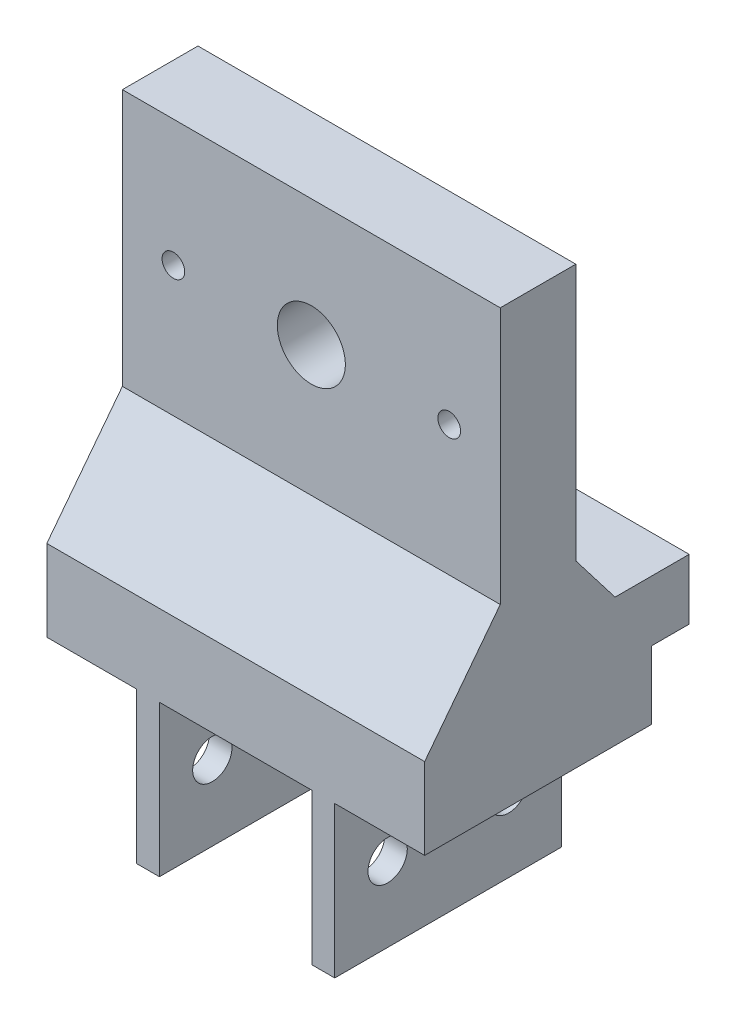
SolidWorks part; units mm, degrees
ref_plane "前视基准面" through (0, 0, 0) normal (0, 0, 1) x (1, 0, 0)
ref_plane "上视基准面" through (0, 0, 0) normal (0, 1, 0) x (1, 0, 0)
ref_plane "右视基准面" through (0, 0, 0) normal (1, 0, 0) x (0, 0, -1)
other "Configuration Table"
sketch "草图1" plane through (0, 0, 0) normal (0, 0, 1) x (1, 0, 0)
  line L0 (0, -39.6057) -> (0, 25.2485) construction
  line L9 (10.1, -25.375) -> (13.1, -25.375)
  line L10 (-25, -5.375) -> (-13.1, -5.375)
  line L11 (-25, -5.375) -> (-25, 5.375)
  line L12 (-25, 5.375) -> (25, 5.375)
  line L13 (25, -5.375) -> (25, 5.375)
  line L14 (-25, -5.375) -> (25, 5.375) construction
  line L15 (-25, 5.375) -> (25, -5.375) construction
  line L16 (-10.1, -5.375) -> (10.1, -5.375)
  line L17 (-13.1, -5.375) -> (-13.1, -25.375)
  line L18 (-13.1, -25.375) -> (-10.1, -25.375)
  line L19 (13.1, -5.375) -> (13.1, -25.375)
  line L21 (-10.1, -25.375) -> (-10.1, -5.375)
  line L22 (-10.1, -5.375) -> (10.1, -5.375)
  line L23 (10.1, -25.375) -> (10.1, -5.375)
  line L24 (-8.4435, -45.2703) -> (10.1, -5.375) construction
  line L25 (-10.1, -5.375) -> (10.5079, -49.7116) construction
  line L26 (-10.1, -5.375) -> (10.1, -5.375)
  line L27 (13.1, -5.375) -> (25, -5.375)
  point P2 (0, 0)
  point P12 (0, -27.1045)
  dimension "D1" = 50
  dimension "D2" = 10.75
  dimension "D3" = 20
  dimension "D4" = 3
  dimension "D5" = 20.2
extrude "凸台-拉伸1" add sketch "草图1" along normal blind 30 contours L19 L27 L13 L12 L11 L10 L17 L18 L21 L16 L23 L9
sketch "草图2" plane through (0, 5.375, 0) normal (0, 1, 0) x (1, 0, 0)
  line L5 (-25, -30) -> (-25, 0) construction
  line L6 (-25, -10) -> (25, -10)
  line L7 (-25, -10) -> (-25, -20)
  line L8 (-25, -20) -> (25, -20)
  line L9 (25, -10) -> (25, -20)
  line L10 (25, -30) -> (25, 0) construction
  line L11 (-25, 0) -> (25, 0) construction
  dimension "D1" = 10
  dimension "D2" = 10
extrude "凸台-拉伸2" add sketch "草图2" along normal blind 50
hole_wizard "孔2" positions "草图8" profile "草图9" legacy end condition through all
sketch "草图8" plane through (-13.1, 0, 0) normal (-1, 0, 0) x (0, 0, 1)
  line L0 (30, -5.375) -> (0, -5.375) construction
  line L1 (0, -5.375) -> (0, -25.375) construction
  line L2 (30, -5.375) -> (30, -25.375) construction
  point P0 (7, -15.375)
  point P2 (23, -15.375)
  dimension "D1" = 10
  dimension "D2" = 10
  dimension "D3" = 7
  dimension "D4" = 7
sketch "草图9" plane through (-13.1, -15.375, 7) normal (0, 1, 0) x (0, 0, 1)
  line L0 (0, 0) -> (0, 38.1)
  line L1 (0, 38.1) -> (2.6, 38.1)
  line L2 (2.6, 38.1) -> (2.6, 0)
  line L3 (2.6, 0) -> (0, 0)
  line L4 (0, 110) -> (0, -10) construction
  dimension "直径" = 5.2
  dimension "深度" = 38.1
hole_wizard "孔3" positions "草图12" profile "草图13" legacy end condition through all
sketch "草图12" plane through (0, 0, 10) normal (0, 0, -1) x (-1, 0, 0)
  line L0 (0, 55.375) -> (0, 5.375) construction
  line L1 (-25, 55.375) -> (25, 55.375) construction
  line L2 (25, 5.375) -> (-25, 5.375) construction
  line L4 (-25, 5.375) -> (25, 5.375) construction
  point P0 (0, 35.625)
  dimension "D1" = 30.25
sketch "草图13" plane through (0, 35.625, 10) normal (1, 0, 0) x (0, 1, 0)
  line L0 (0, 0) -> (0, 20)
  line L1 (0, 20) -> (4.5, 20)
  line L2 (4.5, 20) -> (4.5, 0)
  line L3 (4.5, 0) -> (0, 0)
  line L4 (0, 110) -> (0, -10) construction
  line L5 (-41, 20) -> (-41, -10) construction
  dimension "直径" = 9
  dimension "深度" = 20
sketch "草图17" plane through (0, 0, 10) normal (0, 0, -1) x (-1, 0, 0)
  line L0 (0, 55.375) -> (0, 5.375) construction
  line L1 (-25, 55.375) -> (25, 55.375) construction
  line L2 (25, 5.375) -> (-25, 5.375) construction
  line L3 (-25.3813, 35.625) -> (25.3813, 35.625) construction
  circle A0 centre (18.25, 35.625) radius 2.45
  circle A1 centre (-18.25, 35.625) radius 2.45
  point P10 (0, 35.625)
  dimension "D1" = 4.9
  dimension "D2" = 4.9
  dimension "D3" = 36.5
extrude "凸台-拉伸6" add sketch "草图17" along normal blind 4
hole_wizard "孔5" positions "草图18" profile "草图19" legacy end condition through all
sketch "草图18" plane through (0, 0, 6) normal (0, 0, -1) x (-1, 0, 0)
  point P0 (18.25, 35.625)
  point P3 (-18.25, 35.625)
sketch "草图19" plane through (-18.25, 35.625, 6) normal (1, 0, 0) x (0, 1, 0)
  line L0 (0, 0) -> (0, 24)
  line L1 (0, 24) -> (1.5, 24)
  line L2 (1.5, 24) -> (1.5, 0)
  line L3 (1.5, 0) -> (0, 0)
  line L4 (0, 110) -> (0, -10) construction
  dimension "直径" = 3
  dimension "深度" = 24
sketch "草图20" plane through (-25, 0, 0) normal (-1, 0, 0) x (0, 0, 1)
  line L0 (20, 18.375) -> (30, 5.375)
  line L1 (20, 55.375) -> (20, 5.375) construction
  line L2 (30, -5.375) -> (30, 5.375) construction
  line L3 (30, 5.375) -> (20, 5.375) construction
  line L4 (30, 5.375) -> (20, 5.375)
  line L5 (20, 5.375) -> (20, 18.375)
  line L6 (10, 18.375) -> (0, 5.375)
  line L7 (10, 55.375) -> (10, 5.375) construction
  line L8 (0, 5.375) -> (10, 5.375)
  line L9 (10, 5.375) -> (10, 18.375)
  dimension "D1" = 13
extrude "凸台-拉伸7" add sketch "草图20" against normal up to surface (50 mm away) up to face at (25, 15.1875, 15)
sketch "草图21" plane through (-25, 0, 0) normal (-1, 0, 0) x (0, 0, 1)
  line L0 (10, 55.375) -> (10, 18.375) construction
  line L1 (20, 55.375) -> (10, 55.375)
  line L2 (20, 55.375) -> (20, 52.375)
  line L3 (20, 52.375) -> (10, 52.375)
  line L4 (10, 55.375) -> (10, 52.375)
  dimension "D1" = 3
extrude "切除-拉伸1" cut sketch "草图21" against normal through all
sketch "草图22" plane through (0, 0, 20) normal (0, 0, 1) x (1, 0, 0)
  circle A0 centre (0, 35.625) radius 4.5
  circle A1 centre (0, 35.625) radius 5
  dimension "D1" = 10
sketch "草图23" plane through (25, 0, 0) normal (1, 0, 0) x (0, 0, -1)
  line L0 (26.0243, 3.625) -> (-44.4907, 3.625) construction
  line L1 (-30, -5.375) -> (0, -5.375) construction
  line L2 (5, 17.4661) -> (5, -14.7862) construction
  line L3 (0, -5.375) -> (0, 5.375) construction
  line L4 (0, 5.375) -> (-10, 18.375) construction
  line L5 (5, 3.625) -> (-4.8077, 3.625)
  line L6 (5, 3.625) -> (5, 11.625)
  line L7 (5, 11.625) -> (-4.8077, 11.625)
  line L8 (-4.8077, 3.625) -> (-4.8077, 11.625)
  point P12 (-4.8162, 11.636)
  dimension "D1" = 9
  dimension "D2" = 5
  dimension "D3" = 8
extrude "凸台-拉伸8" add sketch "草图23" against normal up to surface (50 mm away) up to face at (-25, 17.6875, 15)
